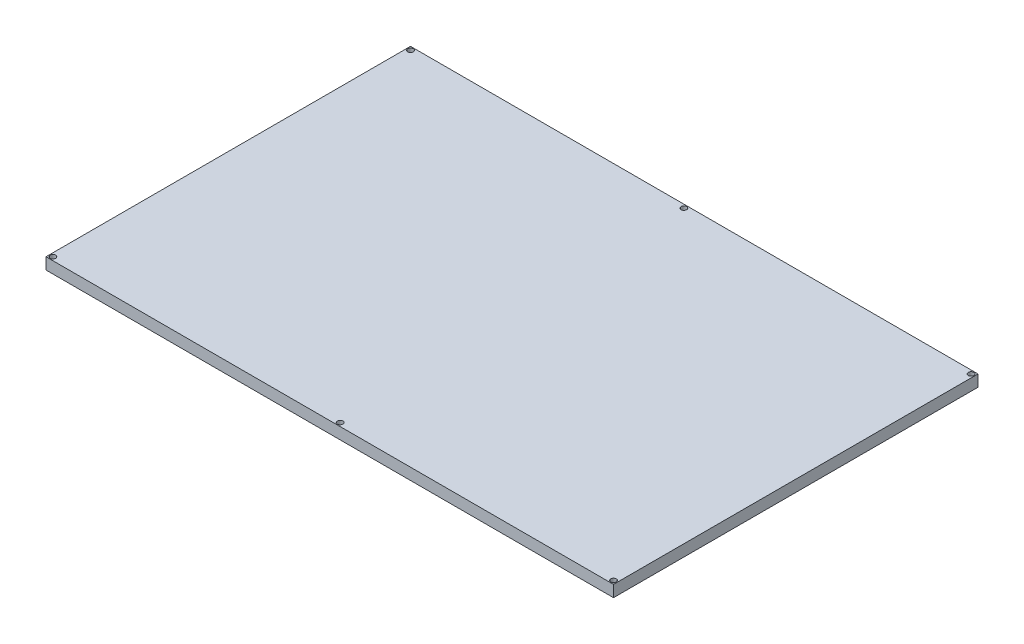
SolidWorks part; units mm, degrees
material "6061 Alloy"
ref_plane "Front Plane" through (0, 0, 0) normal (0, 0, 1) x (1, 0, 0)
ref_plane "Top Plane" through (0, 0, 0) normal (0, 1, 0) x (1, 0, 0)
ref_plane "Right Plane" through (0, 0, 0) normal (1, 0, 0) x (0, 0, -1)
sketch "Sketch1" plane through (0, 0, 0) normal (0, 1, 0) x (1, 0, 0)
  line L0 (-123, 79) -> (123, 79)
  line L7 (123, 79) -> (123, -79)
  line L8 (-123, -79) -> (123, -79)
  line L9 (-123, 79) -> (-123, -79)
  point P0 (0, 0)
extrude "Boss-Extrude1" add sketch "Sketch1" along normal blind 5
hole_wizard "M2 Clearance Hole1" positions "Sketch2" profile "Sketch3" hole size "M2" standard "DIN" end condition through all
sketch "Sketch2" plane through (0, 5, 0) normal (0, 1, 0) x (1, 0, 0)
  line L0 (123, 79) -> (-123, 79) construction
  line L1 (-123, 79) -> (-123, -79) construction
  line L2 (123, -79) -> (123, 79) construction
  line L3 (-123, -79) -> (123, -79) construction
  point P0 (-121.5, 77.5)
  point P2 (-3, 77.5)
  point P4 (121.5, 77.5)
  point P8 (121.5, -77.5)
  point P10 (3, -77.5)
  point P12 (-121.5, -77.5)
  dimension "D1" = 1.5
  dimension "D2" = 1.5
  dimension "D3" = 1.5
  dimension "D4" = 1.5
  dimension "D5" = 1.5
  dimension "D6" = 120
  dimension "D7" = 120
  dimension "D8" = 1.5
  dimension "D9" = 1.5
  dimension "D10" = 1.5
  dimension "D11" = 1.5
  dimension "D12" = 1.5
sketch "Sketch3" plane through (-121.5, 5, -77.5) normal (1, 0, 0) x (0, 0, 1)
  line L0 (0, 0) -> (0, 5)
  line L1 (0, 5) -> (1.2, 5)
  line L2 (1.2, 5) -> (1.2, 0)
  line L5 (1.2, 0) -> (0, 0)
  line L11 (0, -6.35) -> (0, 107.95) construction
  dimension "Thru Hole Dia." = 2.4
  dimension "Thru Hole Depth" = 5
